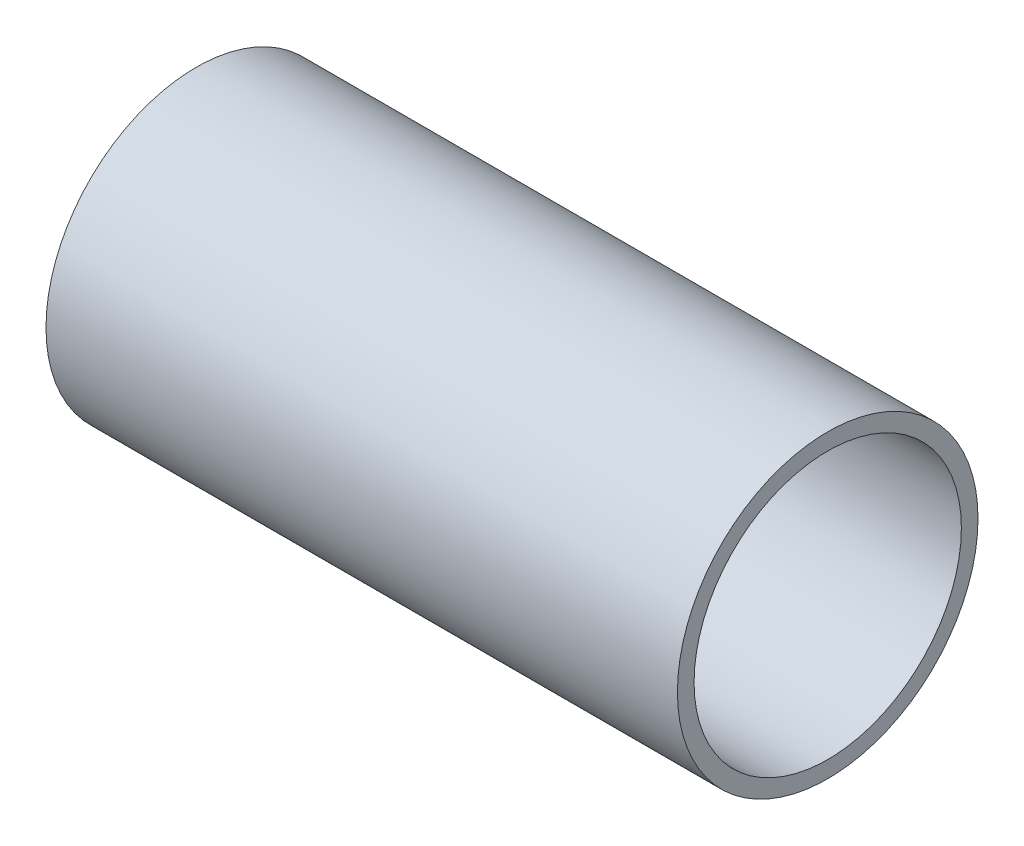
SolidWorks part; units mm, degrees
ref_plane "Front Plane" through (0, 0, 0) normal (0, 0, 1) x (1, 0, 0)
ref_plane "Top Plane" through (0, 0, 0) normal (0, 1, 0) x (1, 0, 0)
ref_plane "Right Plane" through (0, 0, 0) normal (1, 0, 0) x (0, 0, -1)
sketch "Sketch2" plane through (0, 0, 0) normal (1, 0, 0) x (0, 0, -1)
  circle A0 centre (0, 0) radius 6.35
  circle A1 centre (0, 0) radius 7.14
  dimension "D1" = 12.7
  dimension "D2" = 14.28
extrude "Boss-Extrude1" add sketch "Sketch2" along normal blind 30
